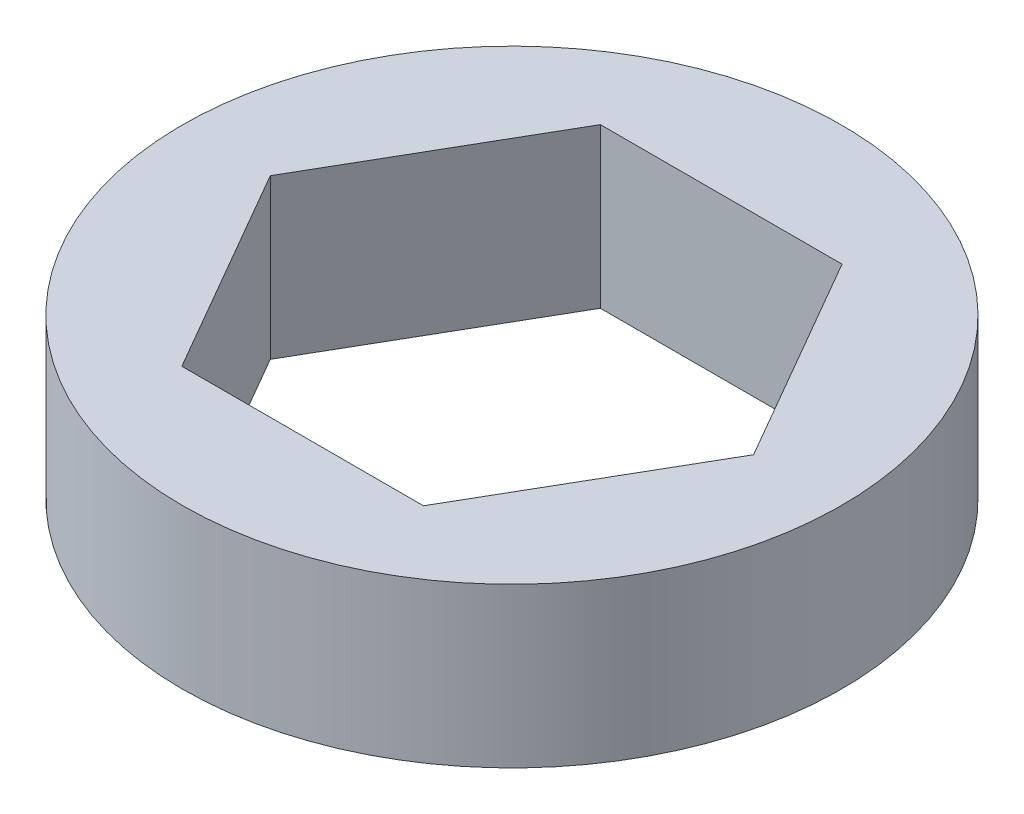
SolidWorks part; units mm, degrees
ref_plane "Front Plane" through (0, 0, 0) normal (0, 0, 1) x (1, 0, 0)
ref_plane "Top Plane" through (0, 0, 0) normal (0, 1, 0) x (1, 0, 0)
ref_plane "Right Plane" through (0, 0, 0) normal (1, 0, 0) x (0, 0, -1)
sketch "Sketch1" plane through (0, 0, 0) normal (0, 1, 0) x (1, 0, 0)
  line L1 (-7.3323, 0) -> (-3.6662, -6.35)
  line L2 (-3.6662, -6.35) -> (3.6662, -6.35)
  line L3 (3.6662, -6.35) -> (7.3323, 0)
  line L4 (7.3323, 0) -> (3.6662, 6.35)
  line L5 (3.6662, 6.35) -> (-3.6662, 6.35)
  line L6 (-3.6662, 6.35) -> (-7.3323, 0)
  circle A0 centre (0, 0) radius 10
  circle A1 centre (0, 0) radius 6.35 construction
  dimension "D2" = 20
  dimension "D1" = 12.7
extrude "Boss-Extrude1" add sketch "Sketch1" along normal blind 4.826
